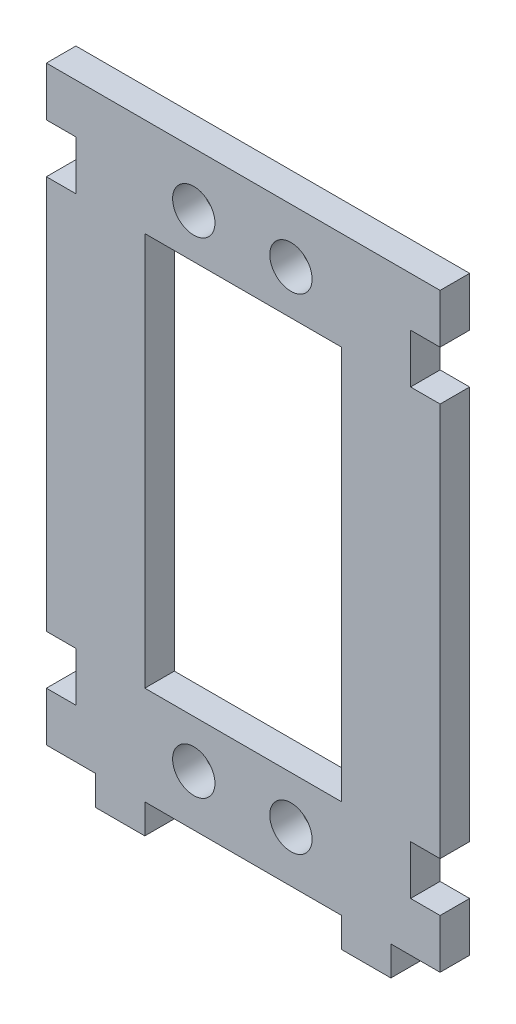
SolidWorks part; units mm, degrees
ref_plane "Front Plane" through (0, 0, 0) normal (0, 0, 1) x (1, 0, 0)
ref_plane "Top Plane" through (0, 0, 0) normal (0, 1, 0) x (1, 0, 0)
ref_plane "Right Plane" through (0, 0, 0) normal (1, 0, 0) x (0, 0, -1)
sketch "Sketch1" plane through (0, 0, 0) normal (0, 0, 1) x (1, 0, 0)
  line L1 (-20, -30) -> (20, -30)
  line L2 (-20, -30) -> (-20, 30)
  line L3 (-20, 30) -> (20, 30)
  line L4 (20, -30) -> (20, 30)
  line L5 (0, 30) -> (0, -30) construction
  line L6 (-20, 0) -> (20, 0) construction
  point P0 (0, 0)
  dimension "D1" = 40
  dimension "D2" = 60
extrude "Boss-Extrude1" add sketch "Sketch1" along normal blind 3
sketch "Sketch2" plane through (0, 0, 3) normal (0, 0, 1) x (1, 0, 0)
  line L1 (-10, -20) -> (10, -20)
  line L2 (-10, -20) -> (-10, 20)
  line L3 (-10, 20) -> (10, 20)
  line L4 (10, -20) -> (10, 20)
  line L5 (0, 20) -> (0, -20) construction
  line L6 (-10, 0) -> (10, 0) construction
  circle A0 centre (4.845, 24.49) radius 2.15
  circle A1 centre (-5.025, 24.49) radius 2.15
  circle A2 centre (-5.025, -24.81) radius 2.15
  circle A3 centre (4.845, -24.81) radius 2.15
  point P0 (0, 0)
  dimension "D1" = 40
  dimension "D2" = 20
extrude "Cut-Extrude1" cut sketch "Sketch2" against normal blind 3
sketch "Sketch3" plane through (0, -30, 0) normal (0, -1, 0) x (1, 0, 0)
  line L0 (-20, 0) -> (20, 0) construction
  line L1 (15, 0) -> (10, 0)
  line L2 (15, 0) -> (15, 3)
  line L3 (15, 3) -> (10, 3)
  line L4 (10, 0) -> (10, 3)
  line L5 (15, 0) -> (15, 3) construction
  line L6 (-20, 3) -> (20, 3) construction
  line L7 (-15, 3) -> (-10, 3)
  line L8 (-15, 3) -> (-15, 0)
  line L9 (-15, 0) -> (-10, 0)
  line L10 (-10, 3) -> (-10, 0)
  line L11 (-15, 3) -> (-15, 0) construction
extrude "Boss-Extrude2" add sketch "Sketch3" along normal blind 3
sketch "Sketch4" plane through (0, 0, 0) normal (0, 0, -1) x (-1, 0, 0)
  line L0 (-20, -30) -> (-20, 30) construction
  line L1 (-17, -25) -> (-20, -25)
  line L2 (-17, -25) -> (-17, -20)
  line L3 (-17, -20) -> (-20, -20)
  line L4 (-20, -25) -> (-20, -20)
  line L5 (-17, -20) -> (-20, -20) construction
  line L6 (-17, 25) -> (-20, 25) construction
  line L7 (-17, 20) -> (-20, 20)
  line L8 (-17, 20) -> (-17, 25)
  line L9 (-17, 25) -> (-20, 25)
  line L10 (-20, 20) -> (-20, 25)
  line L11 (0, 30) -> (0, -33) construction
  line L12 (-20, 30) -> (20, 30) construction
  line L13 (17, 25) -> (20, 25)
  line L14 (20, 20) -> (20, 25)
  line L15 (17, 20) -> (20, 20)
  line L16 (17, 20) -> (17, 25)
  line L17 (17, -20) -> (20, -20)
  line L18 (20, -25) -> (20, -20)
  line L19 (17, -25) -> (20, -25)
  line L20 (17, -25) -> (17, -20)
extrude "Cut-Extrude2" cut sketch "Sketch4" against normal blind 3
